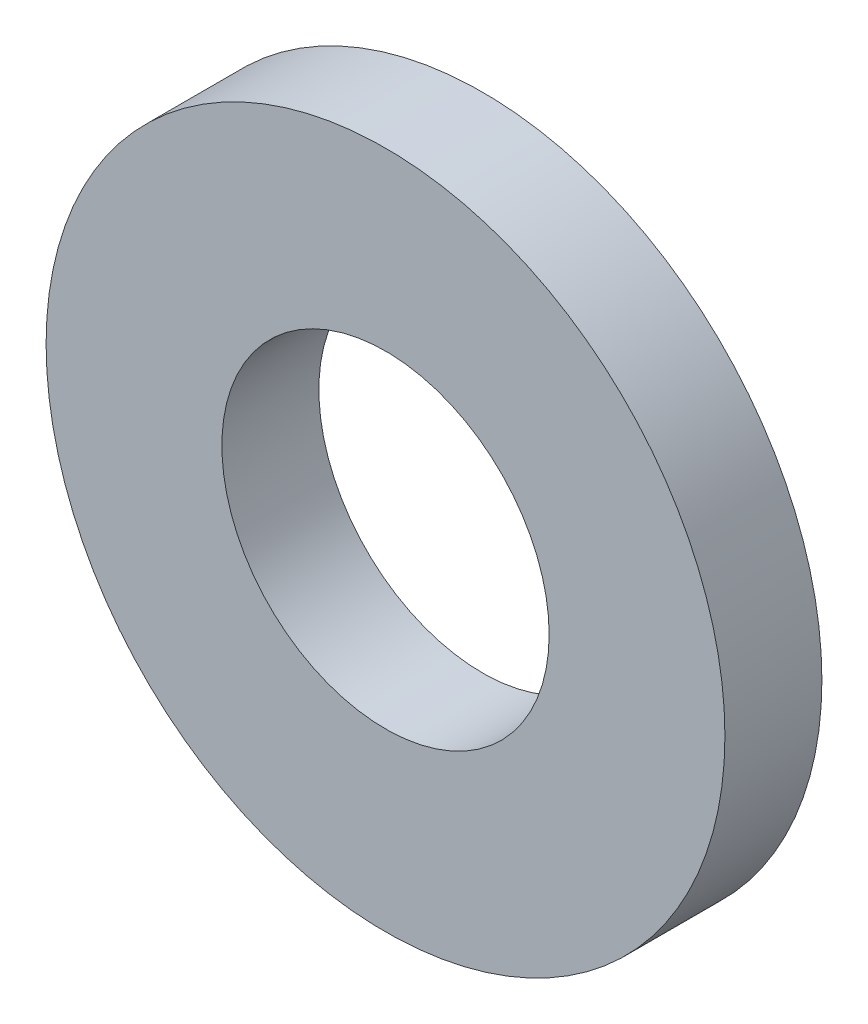
SolidWorks part; units mm, degrees
ref_plane "Front Plane" through (0, 0, 0) normal (0, 0, 1) x (1, 0, 0)
ref_plane "Top Plane" through (0, 0, 0) normal (0, 1, 0) x (1, 0, 0)
ref_plane "Right Plane" through (0, 0, 0) normal (1, 0, 0) x (0, 0, -1)
sketch "Sketch1" plane through (0, 0, 0) normal (0, 0, 1) x (1, 0, 0)
  circle A0 centre (0, 0) radius 2.8 construction
  circle A1 centre (0, 0) radius 1.35 construction
  point P5 (-1.35, 0)
  point P6 (1.35, 0)
  point P7 (2.8, 0)
  point P8 (-2.8, 0)
  dimension "OD" = 5.6
  dimension "ID" = 2.7
sketch "Sketch2" plane through (0, 0, 0) normal (1, 0, 0) x (0, 0, -1)
  line L0 (0.4, 0) -> (-0.4, 0) construction
  line L1 (0, 2.8) -> (0, -2.8) construction
  line L2 (0, 2.8) -> (0, -2.8) construction
  line L3 (0.4, 2.8) -> (-0.4, 2.8) construction
  line L4 (0.4, -2.8) -> (-0.4, -2.8) construction
  line L5 (-0.4, -2.8) -> (-0.4, 2.8) construction
  line L6 (0.4, -2.8) -> (0.4, 2.8) construction
  point P4 (0, 0)
  point P10 (0, 2.8)
  point P11 (-0.4, 2.8)
  point P14 (0, -2.8)
  point P15 (-0.4, -2.8)
  point P16 (0.4, -2.8)
  point P17 (0.4, 2.8)
  point P18 (0.4, 0)
  point P19 (-0.4, 0)
  dimension "Thickness" = 0.8
sketch "Sketch3" plane through (0, 0, 0) normal (0, 0, 1) x (1, 0, 0)
  circle A0 centre (0, 0) radius 2.8 construction
  circle A1 centre (0, 0) radius 1.35 construction
  circle A2 centre (0, 0) radius 2.8
  circle A3 centre (0, 0) radius 1.35
extrude "Boss-Extrude1" add sketch "Sketch3" along normal mid plane 0.8
equation "\"D1@Boss-Extrude1\"=\"Thickness@Sketch2\""
